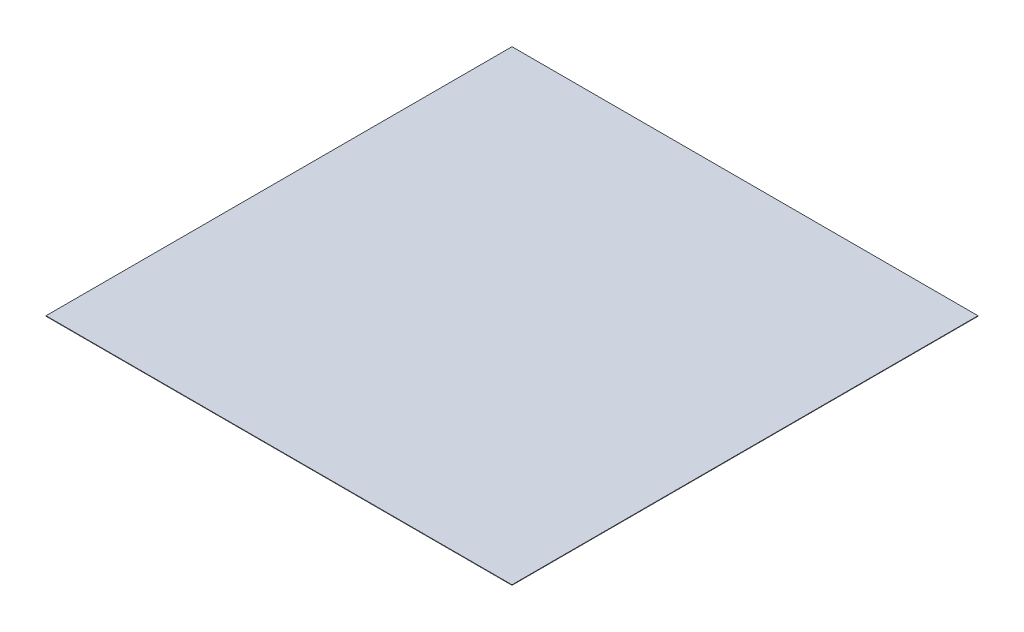
SolidWorks part; units mm, degrees
ref_plane "Front Plane" through (0, 0, 0) normal (0, 0, 1) x (1, 0, 0)
ref_plane "Top Plane" through (0, 0, 0) normal (0, 1, 0) x (1, 0, 0)
ref_plane "Right Plane" through (0, 0, 0) normal (1, 0, 0) x (0, 0, -1)
sketch "Sketch1" plane through (0, 0, 0) normal (0, 1, 0) x (1, 0, 0)
  line L1 (-5000, -5000) -> (5000, -5000)
  line L2 (-5000, -5000) -> (-5000, 5000)
  line L3 (-5000, 5000) -> (5000, 5000)
  line L4 (5000, -5000) -> (5000, 5000)
  line L5 (0, 5000) -> (0, -5000) construction
  line L6 (-5000, 0) -> (5000, 0) construction
  point P0 (0, 0)
  dimension "D1" = 10000
  dimension "D2" = 10000
extrude "Boss-Extrude1" add sketch "Sketch1" along normal blind 10
